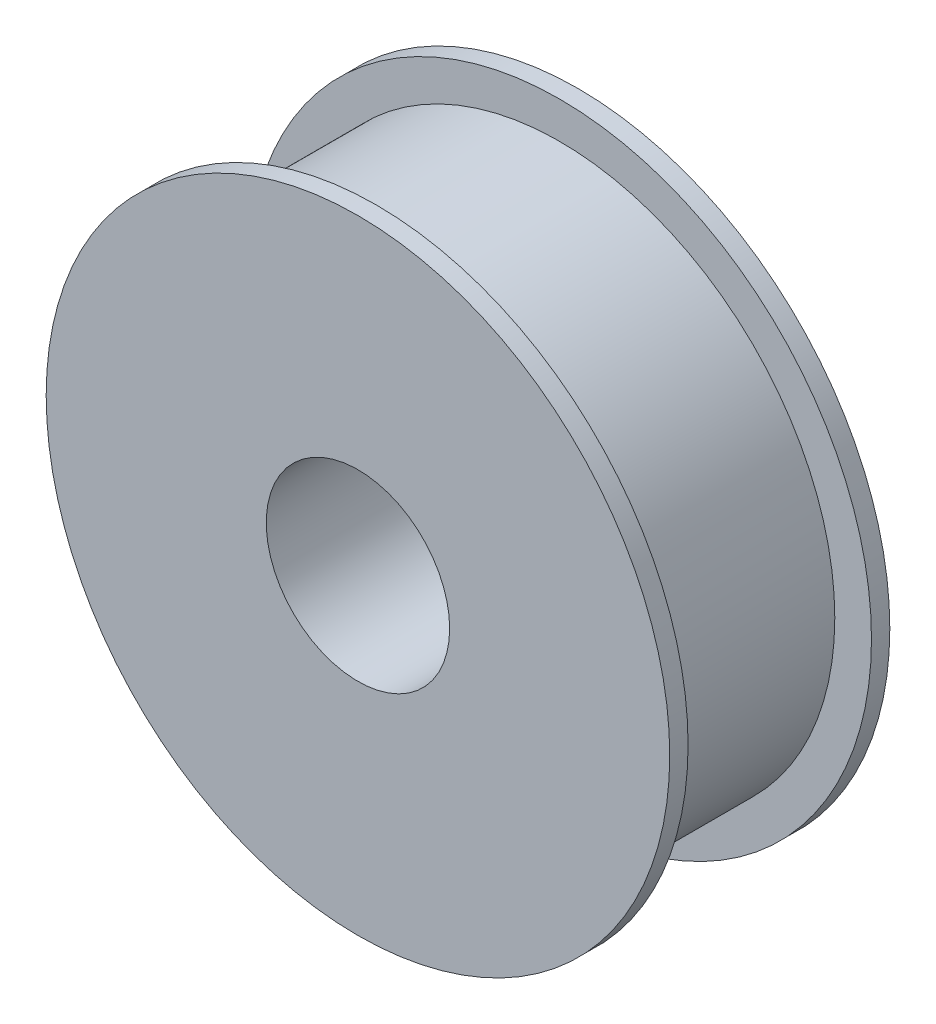
SolidWorks part; units mm, degrees
ref_plane "Front Plane" through (0, 0, 0) normal (0, 0, 1) x (1, 0, 0)
ref_plane "Top Plane" through (0, 0, 0) normal (0, 1, 0) x (1, 0, 0)
ref_plane "Right Plane" through (0, 0, 0) normal (1, 0, 0) x (0, 0, -1)
sketch "Sketch1" plane through (0, 0, 0) normal (1, 0, 0) x (0, 0, -1)
  line L0 (-5, 17) -> (-5, 15)
  line L1 (-6, 17) -> (-5, 17)
  line L2 (-6, 17) -> (-6, 0)
  line L3 (-6, 0) -> (6, 0)
  line L4 (6, 17) -> (6, 0)
  line L9 (-5, 15) -> (5, 15)
  line L10 (5, 15) -> (5, 17)
  line L11 (5, 17) -> (6, 17)
  line L13 (0, 55) -> (0, -55) construction
  point P6 (0, 0)
  dimension "2" = 2
  dimension "D2" = 15
  dimension "D3" = 10
  dimension "D4" = 1
revolve "Revolve1" add sketch "Sketch1" angle 360 about L3
sketch "Sketch3" plane through (0, 0, 0) normal (0, 0, 1) x (1, 0, 0)
  circle A0 centre (0, 0) radius 5
  dimension "D1" = 10
extrude "Cut-Extrude1" cut sketch "Sketch3" against normal through all both and the other way through all
